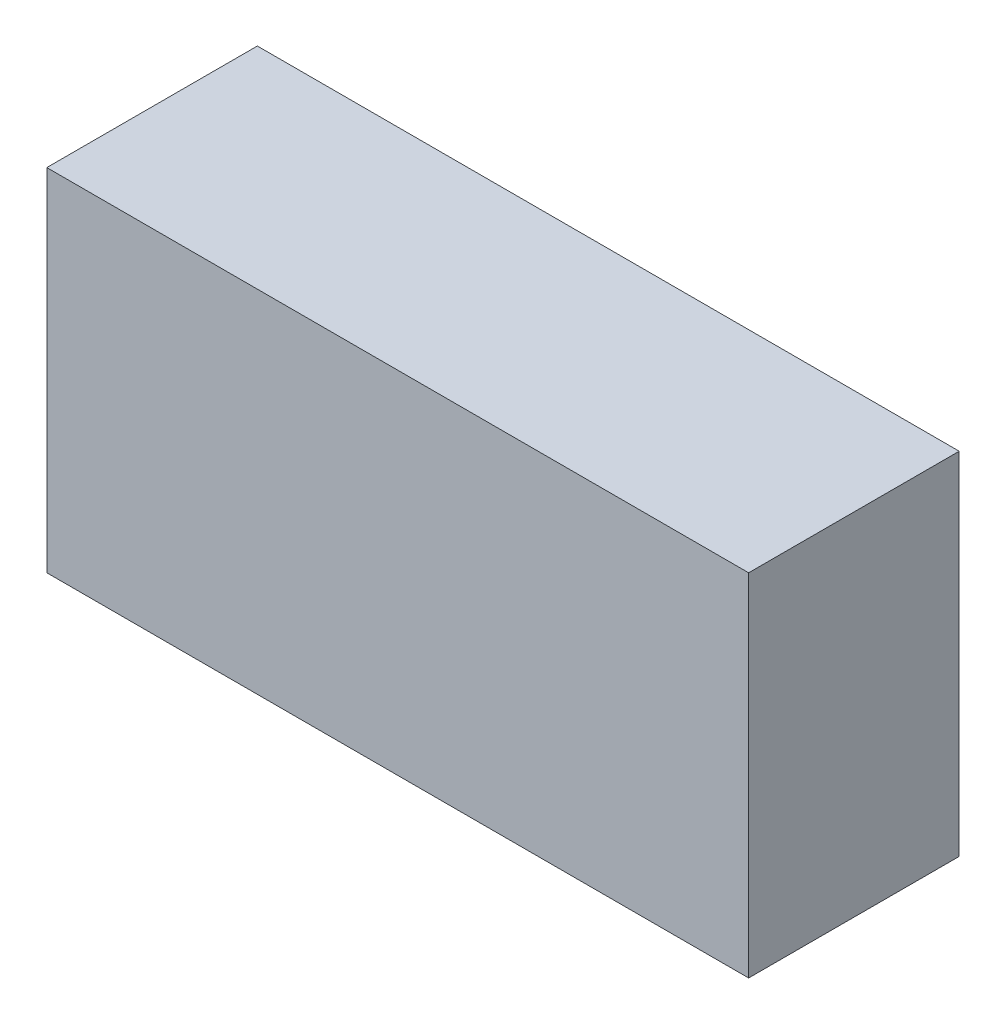
SolidWorks part; units mm, degrees
ref_plane "Спереди" through (0, 0, 0) normal (0, 0, 1) x (1, 0, 0)
ref_plane "Сверху" through (0, 0, 0) normal (0, 1, 0) x (1, 0, 0)
ref_plane "Справа" through (0, 0, 0) normal (1, 0, 0) x (0, 0, -1)
sketch "Эскиз1" plane through (0, 0, 0) normal (0, 0, 1) x (1, 0, 0)
  line L1 (-50, -25) -> (50, -25)
  line L2 (-50, -25) -> (-50, 25)
  line L3 (-50, 25) -> (50, 25)
  line L4 (50, -25) -> (50, 25)
  line L5 (-50, -25) -> (50, 25) construction
  line L6 (-50, 25) -> (50, -25) construction
  point P0 (0, 0)
  dimension "D1" = 100
  dimension "D2" = 50
extrude "Бобышка-Вытянуть1" add sketch "Эскиз1" along normal blind 30
